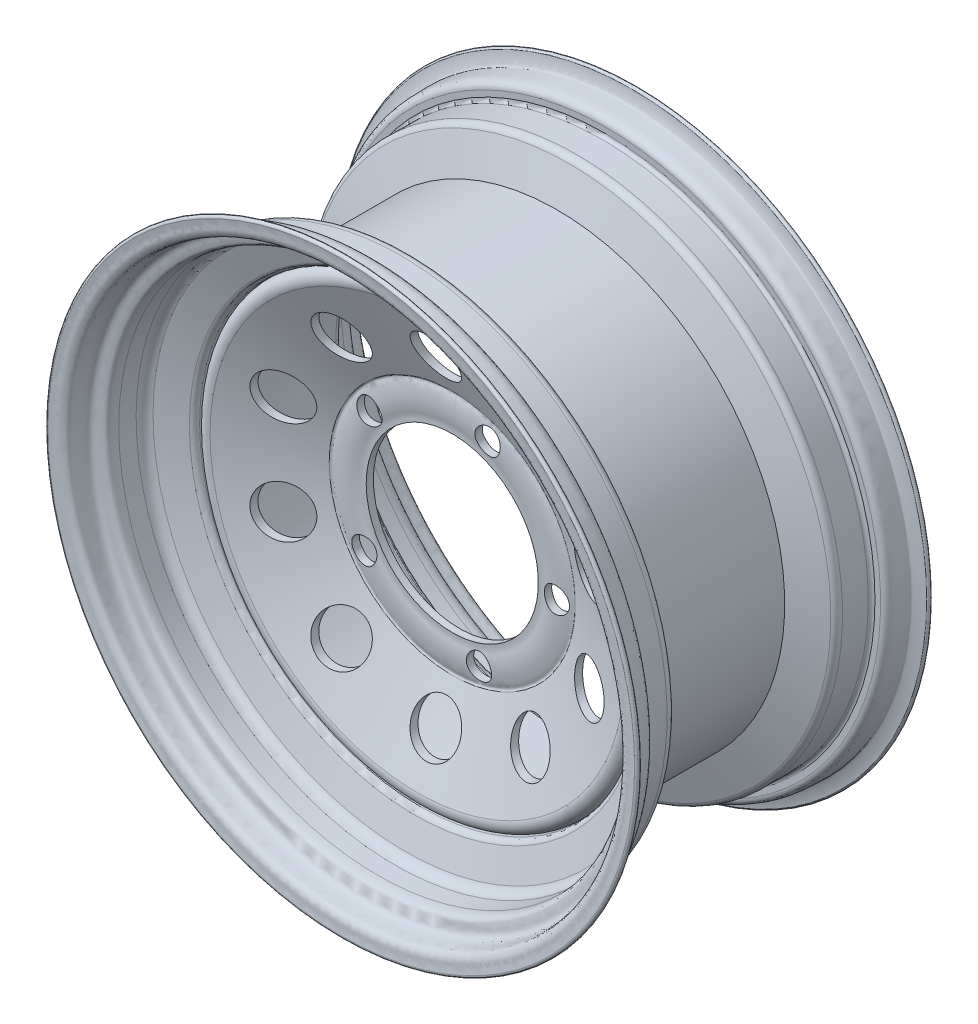
SolidWorks part; units mm, degrees
ref_plane "Front Plane" through (0, 0, 0) normal (0, 0, 1) x (1, 0, 0)
ref_plane "Top Plane" through (0, 0, 0) normal (0, 1, 0) x (1, 0, 0)
ref_plane "Right Plane" through (0, 0, 0) normal (1, 0, 0) x (0, 0, -1)
sketch "Sketch1" plane through (0, 0, 0) normal (1, 0, 0) x (0, 0, -1)
  line L0 (0, 0) -> (200, 0) construction
  line L1 (200, 0) -> (200, -400) construction
  line L2 (100, 0) -> (100, -191.8021) construction
  line L3 (87.5351, -116.8021) -> (87.5351, -141.806) construction
  line L4 (75.1923, -191.8021) -> (75.1923, -116.8004) construction
  line L5 (75.1923, -116.8004) -> (75.1923, -59.9983) construction
  line L6 (75.1923, -59.9983) -> (50.9723, -59.9983) construction
  line L7 (50.9723, -59.9983) -> (50.9723, -50.3732) construction
  line L8 (50.9723, -50.3732) -> (42.0648, -24.764) construction
  line L9 (42.0648, -24.764) -> (17.0122, -24.764) construction
  line L10 (17.0122, -24.764) -> (17.0122, -13.0728) construction
  line L11 (17.0122, -13.0728) -> (0, -13.0728) construction
  line L12 (0, -13.0728) -> (0, 0) construction
  line L13 (24.96, -24.764) -> (36.7236, -24.764)
  line L14 (43.6364, -29.2824) -> (49.972, -47.4974)
  line L15 (57.8785, -50.5642) -> (69.7067, -50.5642)
  line L16 (100, -50.3732) -> (100, -46.0904) construction
  line L17 (139.3416, -46.0904) -> (60.6584, -46.0904)
  line L18 (54.0171, -46.0904) -> (60.6584, -46.0904)
  line L19 (54.0171, -46.0904) -> (45.8389, -23.1062)
  line L20 (40.7014, -20.3399) -> (23.3132, -20.3399)
  line L21 (21.0471, -18.0737) -> (21.0471, -14.2605)
  line L22 (69.7067, -50.5642) -> (69.7067, -55.6257)
  line L23 (69.7067, -55.6257) -> (60.6584, -55.6257)
  line L24 (54.0171, -50.3732) -> (145.9829, -50.3732)
  line L25 (75.1923, -116.8004) -> (51.4573, -59.9983)
  line L26 (100, 0) -> (100, -214.2672) construction
  line L27 (141.7772, -200) -> (75.1923, -200) construction
  line L28 (141.7772, 0) -> (141.7772, -200) construction
  line L29 (75.1923, -191.8021) -> (75.1923, -200) construction
  line L30 (75.1923, -141.7998) -> (80.0236, -141.7998)
  line L31 (79.5156, -114.1785) -> (56.0707, -58.0705)
  line L32 (80.0236, -136.8584) -> (80.0236, -136.6601)
  line L33 (80.0236, -141.7998) -> (80.0236, -136.8584)
  line L34 (60.6584, -55.6257) -> (57.8785, -55.6257)
  line L35 (200, -13.0728) -> (200, 0) construction
  line L36 (182.9878, -13.0728) -> (200, -13.0728) construction
  line L37 (182.9878, -24.764) -> (182.9878, -13.0728) construction
  line L38 (157.9352, -24.764) -> (182.9878, -24.764) construction
  line L39 (149.0277, -50.3732) -> (157.9352, -24.764) construction
  line L41 (178.9529, -18.0737) -> (178.9529, -14.2605)
  line L42 (159.2986, -20.3399) -> (176.6868, -20.3399)
  line L43 (145.9829, -46.0904) -> (154.1611, -23.1062)
  line L44 (145.9829, -46.0904) -> (139.3416, -46.0904)
  line L45 (156.3636, -29.2824) -> (150.028, -47.4974)
  line L46 (175.04, -24.764) -> (163.2764, -24.764)
  line L49 (80.0464, -136.7999) -> (80.0464, -136.7999) construction
  arc A0 (36.7236, -24.764) -> (43.6364, -29.2824) centre (36.7236, -32.3112) cw
  arc A1 (49.972, -47.4974) -> (54.0171, -50.3732) centre (54.0171, -46.0904) ccw
  arc A2 (45.8389, -23.1062) -> (40.7014, -20.3399) centre (41.7401, -24.5646) ccw
  arc A3 (23.3132, -20.3399) -> (21.0471, -18.0737) centre (23.3132, -18.0737) cw
  arc A4 (3.1945, -1.0028) -> (0.1502, -1.7322) centre (1.7234, -1.5804) ccw
  arc A5 (57.8785, -50.5642) -> (51.4573, -59.9983) centre (57.9542, -57.518) ccw
  arc A6 (57.8785, -55.6257) -> (56.0707, -58.0705) centre (57.8785, -57.5165) ccw
  arc A7 (196.8055, -1.0028) -> (199.8498, -1.7322) centre (198.2766, -1.5804) cw
  arc A8 (176.6868, -20.3399) -> (178.9529, -18.0737) centre (176.6868, -18.0737) ccw
  arc A9 (154.1611, -23.1062) -> (159.2986, -20.3399) centre (158.2599, -24.5646) cw
  arc A10 (150.028, -47.4974) -> (145.9829, -50.3732) centre (145.9829, -46.0904) cw
  arc A11 (163.2764, -24.764) -> (156.3636, -29.2824) centre (163.2764, -32.3112) ccw
  spline S0 degree 3 poles (75.1923, -116.8004) (76.3804, -118.0068) (75.4438, -119.0557) (74.5456, -123.2122) (73.9528, -128.3902) (74.5663, -137.2928) (75.5247, -136.8598) (75.1923, -141.7998) knots 0 0 0 0 0.108696 0.14743 0.360682 0.448605 1 1 1 1
  spline S1 degree 3 poles (21.0471, -14.2605) (21.0099, -9.8754) (15.2184, -9.4926) (11.8272, -9.5375) (6.9481, -9.402) (5.1319, -9.3586) (4.6582, -7.3066) (3.9583, -5.057) (3.3784, -2.5371) (3.1945, -1.0028) knots 0 0 0 0 0.243496 0.297374 0.511954 0.561962 0.747448 0.789477 0.959074 0.959074 0.959074 0.959074
  spline S2 degree 3 poles (0.1502, -1.7322) (0.3408, -3.0904) (0.8236, -5.5518) (0.7136, -8.2857) (0.8054, -9.0395) (3.0267, -13.4279) (6.1905, -12.9742) (15.684, -13.3073) (16.7228, -16.2352) (17.3578, -22.0393) (17.4836, -24.8393) (24.96, -24.764) knots 0.011925 0.011925 0.011925 0.011925 0.036092 0.049838 0.138325 0.163506 0.276465 0.325385 0.603788 0.67473 1 1 1 1
  spline S3 degree 1 poles (79.5156, -114.1785) (80.0464, -136.7999) knots 0 0 1 1 construction
  spline S4 degree 3 poles (79.5156, -114.1785) (79.6509, -114.3614) (79.9007, -114.732) (80.3606, -115.5802) (80.7785, -116.7955) (80.9055, -118.2932) (80.7377, -119.5351) (80.4743, -120.429) (80.2438, -121.0207) (80.095, -121.3759) (80.0402, -121.5212) (80.0396, -121.5246) (79.9759, -121.7586) (79.859, -122.3378) (79.7136, -123.1401) (79.5805, -123.9712) (79.4586, -124.8325) (79.3159, -125.9961) (79.1795, -127.4438) (79.0977, -129.0593) (79.1138, -130.8185) (79.3, -132.767) (79.5226, -134.2101) (79.7209, -135.1325) (79.9056, -135.9991) (80.0052, -136.5411) (80.0464, -136.7999) knots 0.010892 0.010892 0.010892 0.010892 0.016801 0.02271 0.034528 0.046346 0.058164 0.069982 0.0818 0.093618 0.105436 0.117254 0.129072 0.152708 0.176345 0.199981 0.223617 0.247253 0.294525 0.341797 0.389069 0.483613 0.578157 0.672701 0.719973 0.767245 0.767245 0.767245 0.767245 only from (79.5156, -114.1785) to (80.0236, -136.6601)
  spline S5 degree 3 poles (199.8498, -1.7322) (199.6592, -3.0904) (199.1764, -5.5518) (199.2864, -8.2857) (199.1946, -9.0395) (196.9733, -13.4279) (193.8095, -12.9742) (184.316, -13.3073) (183.2772, -16.2352) (182.6422, -22.0393) (182.5164, -24.8393) (175.04, -24.764) knots 0.011925 0.011925 0.011925 0.011925 0.036092 0.049838 0.138325 0.163506 0.276465 0.325385 0.603788 0.67473 1 1 1 1
  spline S6 degree 3 poles (178.9529, -14.2605) (178.9901, -9.8754) (184.7816, -9.4926) (188.1728, -9.5375) (193.0519, -9.402) (194.8681, -9.3586) (195.3418, -7.3066) (196.0417, -5.057) (196.6216, -2.5371) (196.8055, -1.0028) knots 0 0 0 0 0.243496 0.297374 0.511954 0.561962 0.747448 0.789477 0.959074 0.959074 0.959074 0.959074
  dimension "D5" = 200
  dimension "D1" = 5
  dimension "D2" = 56.8021
  dimension "D4" = 200
sketch "Sketch2" plane through (0, 0, 0) normal (1, 0, 0) x (0, 0, -1)
  line L0 (75.1923, -141.7998) -> (80.0236, -141.7998)
  line L1 (80.0236, -141.7998) -> (80.0236, -121.5837)
  line L2 (80.0236, -121.5837) -> (79.5156, -114.1785)
  line L3 (79.5156, -114.1785) -> (56.0707, -58.0705)
  line L4 (56.0707, -58.0705) -> (57.8785, -55.6257)
  line L5 (57.8785, -55.6257) -> (69.7067, -55.6257)
  line L6 (69.7067, -55.6257) -> (69.7067, -50.5642)
  line L7 (69.7067, -50.5642) -> (57.8785, -50.5642)
  line L8 (50.9723, -59.9983) -> (75.1923, -116.8004)
  arc A0 (57.8785, -50.5642) -> (50.9723, -59.9983) centre (57.8785, -57.809) ccw
  spline S0 degree 3 poles (79.5156, -114.1785) (79.6509, -114.3614) (79.9007, -114.7319) (80.3606, -115.5802) (80.7786, -116.7955) (80.9055, -118.2932) (80.7377, -119.5351) (80.4743, -120.429) (80.2438, -121.0207) (80.095, -121.3759) (80.0402, -121.5212) (80.0397, -121.5246) (79.9759, -121.7586) (79.859, -122.3378) (79.7136, -123.1401) (79.5805, -123.9712) (79.4587, -124.8325) (79.3159, -125.9961) (79.1795, -127.4438) (79.0977, -129.0593) (79.1139, -130.8185) (79.3001, -132.767) (79.5227, -134.2101) (79.721, -135.1325) (79.8974, -135.9603) (79.9875, -136.445) (80.0236, -136.6601) knots 0.010892 0.010892 0.010892 0.010892 0.016801 0.02271 0.034528 0.046346 0.058164 0.069982 0.0818 0.093618 0.105436 0.117254 0.129072 0.152708 0.176345 0.199981 0.223617 0.247253 0.294525 0.341797 0.389069 0.483613 0.578157 0.672701 0.719973 0.75879 0.75879 0.75879 0.75879 construction
  spline S1 degree 3 poles (75.1923, -116.8004) (76.3379, -117.828) (75.3969, -119.2323) (74.4096, -123.8838) (73.3406, -131.5359) (75.7173, -137.2067) (75.1923, -141.7998) knots 0 0 0 0 0.135685 0.19101 0.553243 1 1 1 1
revolve "Revolve8" add sketch "Sketch1" angle 360 about L27
sketch "Sketch3" plane through (0, 0, 0) normal (0, 0, 1) x (1, 0, 0)
  line L0 (0, -114.1785) -> (0, -58.0705) construction
  circle A0 centre (0, -91.2131) radius 16.13
extrude "Cut-Extrude1" cut sketch "Sketch3" against normal blind 110
pattern_circular "CirPattern1" count 10 over 360 about axis through (0, -200, 0) along (0, 0, 1) of "Cut-Extrude1"
sketch "Sketch4" plane through (0, 0, 0) normal (0, 0, 1) x (1, 0, 0)
  line L0 (0, -200) -> (24.753, -133.5793) construction
  circle A1 centre (24.753, -133.5793) radius 8.5
extrude "Cut-Extrude2" cut sketch "Sketch4" against normal blind 110
pattern_circular "CirPattern2" count 5 over 360 about axis through (0, -200, 0) along (0, 0, 1) of "Cut-Extrude2"
